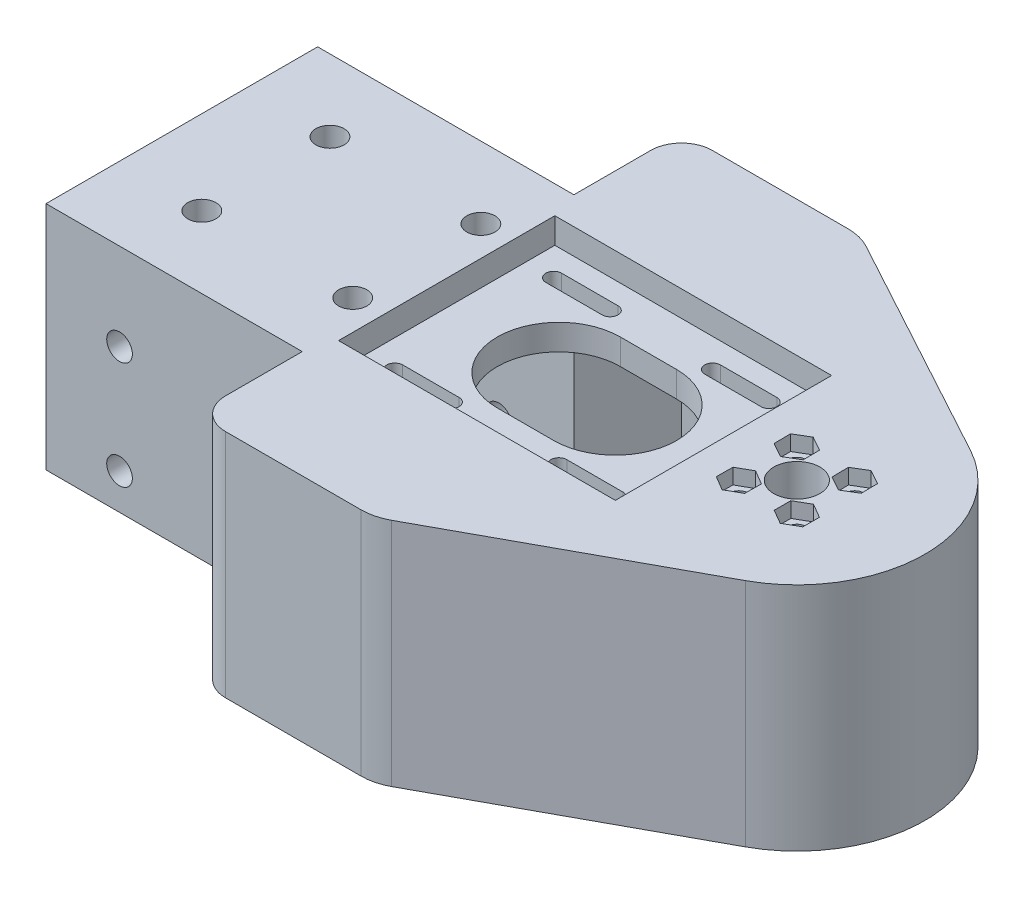
SolidWorks part; units mm, degrees
ref_plane "Front Plane" through (0, 0, 0) normal (0, 0, 1) x (1, 0, 0)
ref_plane "Top Plane" through (0, 0, 0) normal (0, 1, 0) x (1, 0, 0)
ref_plane "Right Plane" through (0, 0, 0) normal (1, 0, 0) x (0, 0, -1)
sketch "Sketch1" plane through (0, 0, 0) normal (0, 1, 0) x (1, 0, 0)
  line L0 (-62.2774, 21.5) -> (-62.2774, -21.5)
  line L1 (-57.2774, 26.5) -> (-17.2774, 26.5)
  line L3 (-12.2774, 31.5) -> (-12.2774, 42.5)
  line L4 (-12.2774, -31.5) -> (-12.2774, -42.5)
  line L5 (-7.2774, 47.5) -> (20.1786, 47.5)
  line L10 (-7.2774, -47.5) -> (20.1786, -47.5)
  line L13 (24.9573, 46.2843) -> (69.6694, 21.9608)
  line L14 (24.9573, -46.2843) -> (69.6694, -21.9608)
  line L16 (-12.2774, -26.5) -> (-12.2774, -31.5)
  line L17 (-17.2774, 26.5) -> (-12.2774, 26.5)
  line L18 (-12.2774, 26.5) -> (-12.2774, 31.5)
  line L19 (-57.2774, -26.5) -> (-12.2774, -26.5)
  line L20 (-57.2774, 26.5) -> (-62.2774, 26.5)
  line L21 (-62.2774, 26.5) -> (-62.2774, 21.5)
  line L22 (-57.2774, -26.5) -> (-62.2774, -26.5)
  line L23 (-62.2774, -26.5) -> (-62.2774, -21.5)
  line L24 (0, 0) -> (86.6614, 0) construction
  line L25 (52.0658, -5.6569) -> (63.3795, 5.6569) construction
  line L26 (52.0658, 5.6569) -> (63.3795, -5.6569) construction
  circle A0 centre (57.7226, 0) radius 4.5
  circle A1 centre (57.7226, 0) radius 8 construction
  arc A7 (-7.2774, -47.5) -> (-12.2774, -42.5) centre (-7.2774, -42.5) cw
  arc A8 (-12.2774, 42.5) -> (-7.2774, 47.5) centre (-7.2774, 42.5) cw
  arc A15 (69.6694, -21.9608) -> (69.6694, 21.9608) centre (57.7226, 0) ccw
  arc A16 (20.1786, 47.5) -> (24.9573, 46.2843) centre (20.1786, 37.5) cw
  arc A17 (24.9573, -46.2843) -> (20.1786, -47.5) centre (20.1786, -37.5) cw
  circle A18 centre (52.0658, -5.6569) radius 1.75
  circle A19 centre (63.3795, 5.6569) radius 1.75
  circle A20 centre (52.0658, 5.6569) radius 1.75
  circle A21 centre (63.3795, -5.6569) radius 1.75
  point P3 (-62.2774, 0)
  point P27 (-12.2774, 47.5)
  point P31 (22.7226, -47.5)
  point P35 (-12.2774, 26.5)
  point P40 (-62.2774, -26.5)
  point P43 (-62.2774, 26.5)
  dimension "D4" = 9
  dimension "D6" = 16
  dimension "D7" = 3.5
  dimension "D8" = 3.5
  dimension "D9" = 3.5
  dimension "D10" = 3.5
  dimension "D11" = 50
  dimension "D12" = 30
  dimension "D13" = 5
  dimension "D14" = 10
  dimension "D15" = 70
  dimension "D1" = 53
  dimension "D2" = 50
  dimension "D3" = 21
  dimension "D5" = 70
  dimension "D16" = 45
  dimension "D17" = 45
extrude "Boss-Extrude1" add sketch "Sketch1" along normal blind 10
sketch "Sketch5" plane through (0, 0, 0) normal (0, -1, 0) x (1, 0, 0)
  line L18 (22.568, -41.8922) -> (67.28, -17.5686)
  line L19 (20.1786, 42.5) -> (-7.2774, 42.5)
  line L20 (-7.2774, 42.5) -> (-7.2774, 21.5)
  line L21 (-7.2774, 21.5) -> (-57.2774, 21.5)
  line L22 (-57.2774, 21.5) -> (-57.2774, -21.5)
  line L23 (-57.2774, -21.5) -> (-7.2774, -21.5)
  line L24 (-7.2774, -21.5) -> (-7.2774, -42.5)
  line L25 (-7.2774, -42.5) -> (20.1786, -42.5)
  line L26 (22.568, -41.8922) -> (67.28, -17.5686)
  line L28 (20.1786, 42.5) -> (-7.2774, 42.5)
  line L29 (-7.2774, 42.5) -> (-7.2774, 21.5)
  line L31 (-57.2774, 21.5) -> (-57.2774, -21.5)
  line L32 (-57.2774, -21.5) -> (-7.2774, -21.5)
  line L33 (-7.2774, -21.5) -> (-7.2774, -42.5)
  line L34 (-7.2774, -42.5) -> (20.1786, -42.5)
  line L36 (67.28, 17.5686) -> (22.568, 41.8922)
  line L37 (67.28, 17.5686) -> (22.568, 41.8922)
  line L38 (-7.2774, 21.5) -> (-57.2774, 21.5)
  arc A18 (20.1786, -42.5) -> (22.568, -41.8922) centre (20.1786, -37.5) ccw
  arc A19 (20.1786, -42.5) -> (22.568, -41.8922) centre (20.1786, -37.5) ccw
  arc A22 (67.28, -17.5686) -> (67.28, 17.5686) centre (57.7226, 0) ccw
  arc A28 (67.28, -17.5686) -> (67.28, 17.5686) centre (57.7226, 0) ccw
  arc A29 (22.568, 41.8922) -> (20.1786, 42.5) centre (20.1786, 37.5) ccw
  arc A30 (22.568, 41.8922) -> (20.1786, 42.5) centre (20.1786, 37.5) ccw
  dimension "D1" = 5
extrude "Extrude-Thin1" add sketch "Sketch5" along normal blind 35 thin
fillet "Fillet2" radius 6 2 edges at (-12.2774, -17.5, -47.5) (-12.2774, -17.5, 47.5)
sketch "Sketch11" plane through (0, 0, 0) normal (0, -1, 0) x (1, 0, 0)
  line L18 (20.1786, 40.5) -> (-5.2774, 40.5)
  line L19 (66.3243, 15.8117) -> (21.6123, 40.1353)
  line L20 (21.6123, -40.1353) -> (66.3243, -15.8117)
  line L21 (-5.2774, -40.5) -> (20.1786, -40.5)
  line L22 (-5.2774, -19.5) -> (-5.2774, -40.5)
  line L23 (-55.2774, -19.5) -> (-5.2774, -19.5)
  line L24 (-55.2774, 19.5) -> (-55.2774, -19.5)
  line L25 (-5.2774, 19.5) -> (-55.2774, 19.5)
  line L26 (-5.2774, 40.5) -> (-5.2774, 19.5)
  line L27 (20.1786, 40.5) -> (-5.2774, 40.5)
  line L28 (66.3243, 15.8117) -> (21.6123, 40.1353)
  line L29 (21.6123, -40.1353) -> (66.3243, -15.8117)
  line L30 (-5.2774, -40.5) -> (20.1786, -40.5)
  line L31 (-5.2774, -19.5) -> (-5.2774, -40.5)
  line L32 (-55.2774, -19.5) -> (-5.2774, -19.5)
  line L33 (-55.2774, 19.5) -> (-55.2774, -19.5)
  line L34 (-5.2774, 19.5) -> (-55.2774, 19.5)
  line L35 (-5.2774, 40.5) -> (-5.2774, 19.5)
  arc A6 (21.6123, 40.1353) -> (20.1786, 40.5) centre (20.1786, 37.5) ccw
  arc A7 (66.3243, -15.8117) -> (66.3243, 15.8117) centre (57.7226, 0) ccw
  arc A8 (20.1786, -40.5) -> (21.6123, -40.1353) centre (20.1786, -37.5) ccw
  arc A9 (21.6123, 40.1353) -> (20.1786, 40.5) centre (20.1786, 37.5) ccw
  arc A10 (66.3243, -15.8117) -> (66.3243, 15.8117) centre (57.7226, 0) ccw
  arc A11 (20.1786, -40.5) -> (21.6123, -40.1353) centre (20.1786, -37.5) ccw
  dimension "D1" = 2
extrude "Extrude-Thin2" add sketch "Sketch11" along normal blind 35 thin
sketch "Sketch7" plane through (0, 0, 26.5) normal (0, 0, 1) x (1, 0, 0)
  circle A0 centre (-47.9289, -7) radius 2.5
  circle A1 centre (-19.9289, -7) radius 2.5
  circle A2 centre (-19.9289, -28) radius 2.5
  circle A3 centre (-47.9289, -28) radius 2.5
  dimension "D1" = 5
extrude "Cut-Extrude2" cut sketch "Sketch7" against normal blind 10
sketch "Sketch20" plane through (0, 10, 0) normal (0, 1, 0) x (1, 0, 0)
  line L1 (54.8838, -4.0719) -> (52.1021, -2.4239)
  line L2 (52.1021, -2.4239) -> (49.2841, -4.0089)
  line L3 (49.2841, -4.0089) -> (49.2478, -7.2419)
  line L4 (49.2478, -7.2419) -> (52.0294, -8.8898)
  line L5 (52.0294, -8.8898) -> (54.8474, -7.3048)
  line L6 (54.8474, -7.3048) -> (54.8838, -4.0719)
  line L7 (54.8862, 4.0761) -> (54.8449, 7.309)
  line L8 (54.8449, 7.309) -> (52.0245, 8.8898)
  line L9 (52.0245, 8.8898) -> (49.2454, 7.2376)
  line L10 (49.2454, 7.2376) -> (49.2866, 4.0047)
  line L11 (49.2866, 4.0047) -> (52.107, 2.424)
  line L12 (52.107, 2.424) -> (54.8862, 4.0761)
  line L13 (66.1749, -7.2813) -> (66.184, -4.0481)
  line L14 (66.184, -4.0481) -> (63.3885, -2.4237)
  line L15 (63.3885, -2.4237) -> (60.584, -4.0324)
  line L16 (60.584, -4.0324) -> (60.575, -7.2656)
  line L17 (60.575, -7.2656) -> (63.3704, -8.89)
  line L18 (63.3704, -8.89) -> (66.1749, -7.2813)
  line L19 (66.2041, 4.0838) -> (66.1542, 7.3165)
  line L20 (66.1542, 7.3165) -> (63.3295, 8.8896)
  line L21 (63.3295, 8.8896) -> (60.5548, 7.23)
  line L22 (60.5548, 7.23) -> (60.6048, 3.9972)
  line L23 (60.6048, 3.9972) -> (63.4295, 2.4241)
  line L24 (63.4295, 2.4241) -> (66.2041, 4.0838)
  circle A0 centre (52.0658, -5.6569) radius 2.8 construction
  circle A1 centre (52.0658, 5.6569) radius 2.8 construction
  circle A2 centre (63.3795, -5.6569) radius 2.8 construction
  circle A3 centre (63.3795, 5.6569) radius 2.8 construction
  dimension "D1" = 5.6
  dimension "D2" = 5.6
  dimension "D3" = 5.6
  dimension "D4" = 5.6
extrude "Cut-Extrude13" cut sketch "Sketch20" against normal blind 3
mirror "Mirror1" about plane through (0, 0, 0) normal (0, 0, 1) of "Cut-Extrude2"
sketch "Sketch12" plane through (0, 10, 0) normal (0, 1, 0) x (1, 0, 0)
  circle A0 centre (-45.8721, -12.5) radius 2.75
  circle A1 centre (-45.8721, 12.5) radius 2.75
  circle A2 centre (-16.4289, 12.5) radius 2.75
  circle A3 centre (-16.4289, -12.5) radius 2.75
extrude "Cut-Extrude5" cut sketch "Sketch12" against normal up to next
sketch "Sketch13" plane through (0, 0, 0) normal (0, -1, 0) x (1, 0, 0)
  line L1 (-41.713, -9.8952) -> (-46.0484, -7.5957)
  line L2 (-46.0484, -7.5957) -> (-50.2075, -10.2005)
  line L3 (-50.2075, -10.2005) -> (-50.0312, -15.1048)
  line L4 (-50.0312, -15.1048) -> (-45.6958, -17.4043)
  line L5 (-45.6958, -17.4043) -> (-41.5367, -14.7995)
  line L6 (-41.5367, -14.7995) -> (-41.713, -9.8952)
  line L7 (-41.7074, 9.9041) -> (-41.5416, 14.8088)
  line L8 (-41.5416, 14.8088) -> (-45.7063, 17.4047)
  line L9 (-45.7063, 17.4047) -> (-50.0368, 15.0959)
  line L10 (-50.0368, 15.0959) -> (-50.2026, 10.1912)
  line L11 (-50.2026, 10.1912) -> (-46.0379, 7.5953)
  line L12 (-46.0379, 7.5953) -> (-41.7074, 9.9041)
  line L13 (-12.2942, -9.8566) -> (-16.6508, -7.5975)
  line L14 (-16.6508, -7.5975) -> (-20.7855, -10.2409)
  line L15 (-20.7855, -10.2409) -> (-20.5636, -15.1434)
  line L16 (-20.5636, -15.1434) -> (-16.207, -17.4025)
  line L17 (-16.207, -17.4025) -> (-12.0723, -14.7591)
  line L18 (-12.0723, -14.7591) -> (-12.2942, -9.8566)
  line L19 (-12.2974, 9.8516) -> (-12.0695, 14.7538)
  line L20 (-12.0695, 14.7538) -> (-16.201, 17.4022)
  line L21 (-16.201, 17.4022) -> (-20.5604, 15.1484)
  line L22 (-20.5604, 15.1484) -> (-20.7882, 10.2462)
  line L23 (-20.7882, 10.2462) -> (-16.6567, 7.5978)
  line L24 (-16.6567, 7.5978) -> (-12.2974, 9.8516)
  circle A0 centre (-45.8721, -12.5) radius 4.25 construction
  circle A1 centre (-45.8721, 12.5) radius 4.25 construction
  circle A2 centre (-16.4289, -12.5) radius 4.25 construction
  circle A3 centre (-16.4289, 12.5) radius 4.25 construction
  dimension "D1" = 8.5
  dimension "D2" = 8.5
  dimension "D3" = 8.5
  dimension "D4" = 8.5
extrude "Cut-Extrude6" cut sketch "Sketch13" against normal blind 2
sketch "Sketch14" plane through (0, 10, 0) normal (0, 1, 0) x (1, 0, 0)
  line L1 (43.4062, -21.1) -> (-10.5938, -21.1)
  line L2 (43.4062, -21.1) -> (43.4062, 21.1)
  line L3 (43.4062, 21.1) -> (-10.5938, 21.1)
  line L4 (-10.5938, -21.1) -> (-10.5938, 21.1)
  line L9 (-12.2774, -26.5) -> (-12.2774, -41.5) construction
  point P4 (-10.5938, 0)
  dimension "D1" = 1.6836
  dimension "D2" = 42.2
  dimension "D3" = 54
extrude "Cut-Extrude7" cut sketch "Sketch14" against normal blind 5
sketch "Sketch15" plane through (0, 5, 0) normal (0, 1, 0) x (1, 0, 0)
  line L0 (11.2802, 0) -> (22.2802, 0) construction
  line L1 (11.2802, 0) -> (22.2802, 0) construction
  line L2 (11.2802, 12) -> (22.2802, 12)
  line L3 (11.2802, -12) -> (22.2802, -12)
  line L4 (26.7802, -15.5) -> (37.7802, -15.5) construction
  line L10 (-10.5938, 21.1) -> (-10.5938, -21.1) construction
  line L11 (26.7802, -13.95) -> (37.7802, -13.95)
  line L12 (26.7802, -17.05) -> (37.7802, -17.05)
  line L13 (-5.2198, -15.5) -> (5.7802, -15.5) construction
  line L14 (-5.2198, -13.95) -> (5.7802, -13.95)
  line L15 (-5.2198, -17.05) -> (5.7802, -17.05)
  line L16 (-5.2198, 15.5) -> (5.7802, 15.5) construction
  line L17 (-5.2198, 17.05) -> (5.7802, 17.05)
  line L18 (-5.2198, 13.95) -> (5.7802, 13.95)
  line L19 (25.7802, 15.5) -> (36.7802, 15.5) construction
  line L20 (25.7802, 17.05) -> (36.7802, 17.05)
  line L21 (25.7802, 13.95) -> (36.7802, 13.95)
  arc A1 (11.2802, 12) -> (11.2802, -12) centre (11.2802, 0) ccw
  arc A2 (22.2802, -12) -> (22.2802, 12) centre (22.2802, 0) ccw
  arc A7 (26.7802, -13.95) -> (26.7802, -17.05) centre (26.7802, -15.5) ccw
  arc A8 (37.7802, -17.05) -> (37.7802, -13.95) centre (37.7802, -15.5) ccw
  arc A9 (-5.2198, -13.95) -> (-5.2198, -17.05) centre (-5.2198, -15.5) ccw
  arc A10 (5.7802, -17.05) -> (5.7802, -13.95) centre (5.7802, -15.5) ccw
  arc A11 (-5.2198, 17.05) -> (-5.2198, 13.95) centre (-5.2198, 15.5) ccw
  arc A12 (5.7802, 13.95) -> (5.7802, 17.05) centre (5.7802, 15.5) ccw
  arc A13 (25.7802, 17.05) -> (25.7802, 13.95) centre (25.7802, 15.5) ccw
  arc A14 (36.7802, 13.95) -> (36.7802, 17.05) centre (36.7802, 15.5) ccw
  point P1 (16.7802, 0)
  point P8 (11.2802, 0)
  point P13 (32.2802, -15.5)
  point P19 (0.2802, -15.5)
  point P25 (0.2802, 15.5)
  point P31 (31.2802, 15.5)
  dimension "D1" = 37.374
  dimension "D4" = 5.374
  dimension "D2" = 5.374
  dimension "D3" = 31
  dimension "D5" = 36.374
  dimension "D6" = 21.874
extrude "Cut-Extrude8" cut sketch "Sketch15" against normal up to next
sketch "Sketch17" plane through (-62.2774, 0, 0) normal (-1, 0, 0) x (0, 0, 1)
  line L0 (-26.5, 10) -> (26.5, 10) construction
  line L1 (-9.5, 0) -> (9.5, 0)
  line L2 (-9.5, 0) -> (-9.5, -25)
  line L3 (-9.5, -25) -> (9.5, -25)
  line L4 (9.5, 0) -> (9.5, -25)
  line L5 (-26.5, 10) -> (-26.5, -35) construction
  point P4 (0, 0)
  point P7 (0, 10)
  point P8 (-9.5, -12.5)
  point P11 (-26.5, -12.5)
  dimension "D1" = 19
  dimension "D2" = 25
sketch "Sketch22" plane through (-62.2774, 0, 0) normal (-1, 0, 0) x (0, 0, 1)
  circle A1 centre (-14.5, -18.75) radius 2.55
  circle A3 centre (14.5, -18.75) radius 2.55
extrude "Cut-Extrude10" cut sketch "Sketch17" against normal up to next
sketch "Sketch18" plane through (-62.2774, 0, 0) normal (-1, 0, 0) x (0, 0, 1)
  line L0 (-14.5, -6.25) -> (-14.5, -18.75) construction
  line L1 (14.5, -6.25) -> (14.5, -18.75) construction
  line L2 (-26.5, 10) -> (-26.5, -35) construction
  line L3 (-14.5, -12.5) -> (14.5, -12.5) construction
  line L4 (-26.5, 10) -> (26.5, 10) construction
  circle A0 centre (-14.5, -6.25) radius 2.55
  circle A1 centre (-14.5, -18.75) radius 2.55
  circle A2 centre (14.5, -6.25) radius 2.55
  circle A3 centre (14.5, -18.75) radius 2.55
  point P8 (-14.5, -12.5)
  point P11 (-26.5, -12.5)
  point P12 (14.5, -12.5)
  point P15 (0, -12.5)
  point P18 (0, 10)
  dimension "D1" = 5.1
  dimension "D2" = 29
  dimension "D3" = 16.25
  dimension "D4" = 12.5
extrude "Cut-Extrude12" cut sketch "Sketch18" against normal up to next
sketch "Sketch23" plane through (0, 0, -19.5) normal (0, 0, 1) x (1, 0, 0)
  circle A0 centre (-47.9289, -7) radius 5.5
  circle A1 centre (-47.9289, -28) radius 5.5
  dimension "D1" = 11
extrude "Cut-Extrude14" cut sketch "Sketch23" against normal blind 1
sketch "Sketch25" plane through (0, 0, 19.5) normal (0, 0, -1) x (-1, 0, 0)
  circle A0 centre (47.9289, -7) radius 5.5
  circle A1 centre (47.9289, -28) radius 5.5
  dimension "D1" = 11
  dimension "D2" = 11
extrude "Cut-Extrude15" cut sketch "Sketch25" against normal blind 1
sketch "Sketch26" plane through (0, 0, -19.5) normal (0, 0, 1) x (1, 0, 0)
  line L1 (-38.0042, -21.8038) -> (-28.0042, -21.8038)
  line L2 (-38.0042, -21.8038) -> (-38.0042, -25.8038)
  line L3 (-38.0042, -25.8038) -> (-28.0042, -25.8038)
  line L4 (-28.0042, -21.8038) -> (-28.0042, -25.8038)
  dimension "D1" = 10
  dimension "D2" = 4
extrude "Boss-Extrude2" add sketch "Sketch26" along normal blind 7
sketch "Sketch27" plane through (0, -21.8038, 0) normal (0, 1, 0) x (1, 0, 0)
  line L0 (-38.0042, 12.5) -> (-38.0042, 19.5) construction
  line L1 (-28.0042, 12.5) -> (-38.0042, 12.5)
  line L2 (-28.0042, 12.5) -> (-28.0042, 15.5)
  line L3 (-28.0042, 15.5) -> (-38.0042, 15.5)
  line L4 (-38.0042, 12.5) -> (-38.0042, 15.5)
  dimension "D1" = 3
extrude "Boss-Extrude3" add sketch "Sketch27" along normal blind 5
sketch "Sketch29" plane through (21.7832, 0, -40.0423) normal (-0.4779, 0, 0.8784) x (0.8784, 0, 0.4779)
  line L0 (-42.7026, -25.8038) -> (-33.9183, -25.8038) construction
  line L1 (10.5209, -15.8038) -> (30.5209, -15.8038)
  line L2 (10.5209, -15.8038) -> (10.5209, -25.8038)
  line L3 (10.5209, -25.8038) -> (30.5209, -25.8038)
  line L4 (30.5209, -15.8038) -> (30.5209, -25.8038)
  dimension "D1" = 10
  dimension "D2" = 20
extrude "Cut-Extrude17" cut sketch "Sketch29" against normal up to next
